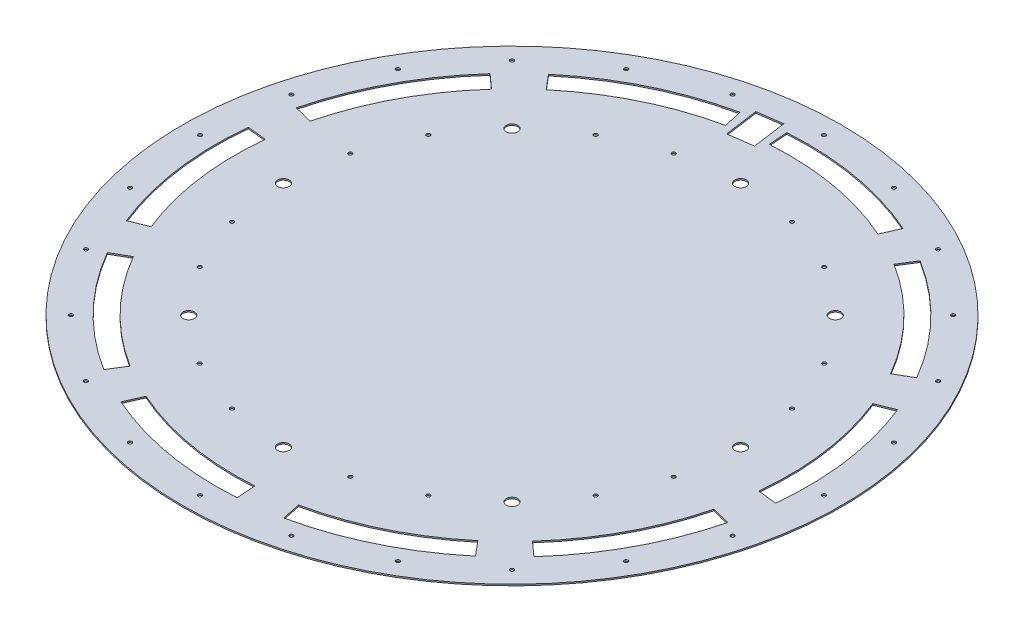
SolidWorks part; units mm, degrees
ref_plane "Front Plane" through (0, 0, 0) normal (0, 0, 1) x (1, 0, 0)
ref_plane "Top Plane" through (0, 0, 0) normal (0, 1, 0) x (1, 0, 0)
ref_plane "Right Plane" through (0, 0, 0) normal (1, 0, 0) x (0, 0, -1)
sketch "Sketch1" plane through (0, 0, 0) normal (0, 1, 0) x (1, 0, 0)
  line L0 (0, -1000) -> (0, 49000) construction
  line L1 (-1000, 0) -> (49000, 0) construction
  line L2 (0, 0) -> (-231.8222, 62.1166) construction
  line L3 (-231.8222, 62.1166) -> (-316.3407, 84.7632) construction
  line L4 (0, 0) -> (-45.5792, 324.3128) construction
  line L5 (-57.1305, 313.096) -> (-31.3836, 316.7145)
  line L6 (-31.3836, 316.7145) -> (-26.3733, 281.0648)
  line L7 (-26.3733, 281.0648) -> (-52.1203, 277.4463)
  line L8 (-52.1203, 277.4463) -> (-57.1305, 313.096)
  line L9 (-52.1203, 277.4463) -> (-31.3836, 316.7145) construction
  line L10 (-57.1305, 313.096) -> (-26.3733, 281.0648) construction
  line L11 (-20.2991, 290.2911) -> (-21.6943, 310.2424)
  line L13 (126.4951, 284.1126) -> (118.3604, 265.8417)
  line L14 (0, 0) -> (118.3604, 265.8417) construction
  line L15 (269.3339, 155.5) -> (252.0134, 145.5)
  line L16 (154.2065, 246.782) -> (164.8049, 263.743)
  line L17 (309.2963, -32.5084) -> (289.4059, -30.4178)
  line L18 (269.8105, 109.0105) -> (288.3542, 116.5027)
  line L19 (231.118, -208.0996) -> (216.2551, -194.717)
  line L20 (282.3561, -70.3993) -> (301.762, -75.2377)
  line L21 (64.6605, -304.2039) -> (60.5023, -284.641)
  line L22 (187.0512, -222.9189) -> (199.9069, -238.2398)
  line L23 (-126.4951, -284.1126) -> (-118.3604, -265.8417)
  line L24 (20.2991, -290.2911) -> (21.6943, -310.2424)
  line L25 (-269.3339, -155.5) -> (-252.0134, -145.5)
  line L26 (-154.2065, -246.782) -> (-164.8049, -263.743)
  line L27 (-309.2963, 32.5084) -> (-289.4059, 30.4178)
  line L28 (-269.8105, -109.0105) -> (-288.3542, -116.5027)
  line L29 (-231.118, 208.0996) -> (-216.2551, 194.717)
  line L30 (-282.3561, 70.3993) -> (-301.762, 75.2377)
  line L31 (-64.6605, 304.2039) -> (-60.5023, 284.641)
  line L32 (-187.0512, 222.9189) -> (-199.9069, 238.2398)
  circle A0 centre (0, 0) radius 346
  circle A2 centre (0, 240) radius 6
  circle A3 centre (169.7056, 169.7056) radius 6
  circle A4 centre (240, 0) radius 6
  circle A5 centre (169.7056, -169.7056) radius 6
  circle A6 centre (0, -240) radius 6
  circle A7 centre (-169.7056, -169.7056) radius 6
  circle A8 centre (-240, 0) radius 6
  circle A9 centre (-169.7056, 169.7056) radius 6
  circle A10 centre (0, 0) radius 240 construction
  circle A11 centre (-231.8222, 62.1166) radius 2
  circle A12 centre (-207.8461, 120.0003) radius 2
  circle A14 centre (-119.9997, 207.8468) radius 2
  circle A15 centre (-62.1161, 231.8231) radius 2
  circle A17 centre (62.1176, 231.8232) radius 2
  circle A18 centre (120.0013, 207.8471) radius 2
  circle A20 centre (207.8478, 120.0007) radius 2
  circle A21 centre (231.8241, 62.1171) radius 2
  circle A23 centre (231.8242, -62.1166) radius 2
  circle A24 centre (207.8481, -120.0003) radius 2
  circle A26 centre (120.0017, -207.8468) radius 2
  circle A27 centre (62.1181, -231.8231) radius 2
  circle A29 centre (-62.1156, -231.8232) radius 2
  circle A30 centre (-119.9993, -207.8471) radius 2
  circle A32 centre (-207.8458, -120.0007) radius 2
  circle A33 centre (-231.8221, -62.1171) radius 2
  arc A35 (-168.2848, -171.1146) -> (-171.1133, -168.2862) centre (-169.7051, -169.7065) ccw [skipped]
  arc A36 (-1.9987, -239.9917) -> (0, -242.001) centre (0.0013, -240.001) ccw [skipped]
  arc A37 (168.2862, -171.1133) -> (171.1146, -168.2849) centre (169.7075, -169.7061) ccw [skipped]
  arc A38 (238.002, 0) -> (239.9917, -1.9997) centre (240.002, 0.0003) ccw [skipped]
  arc A39 (171.1142, 168.2852) -> (168.2859, 171.1136) centre (169.7071, 169.7065) ccw [skipped]
  arc A40 (-1.9992, 239.9917) -> (-1.4433, 238.6172) centre (0.0007, 240.001) ccw [skipped]
  arc A41 (-168.2852, 171.1142) -> (-171.1136, 168.2859) centre (-169.7055, 169.7061) ccw [skipped]
  arc A42 (-239.9917, -2.0002) -> (-238, 0) centre (-240, -0.0003) ccw [skipped]
  circle A43 centre (0, 0) radius 327.5 construction
  circle A44 centre (-316.3407, 84.7632) radius 2
  circle A45 centre (-283.6233, 163.75) radius 2
  circle A46 centre (-231.5775, 231.5775) radius 2
  circle A47 centre (-163.75, 283.6233) radius 2
  circle A48 centre (-84.7632, 316.3407) radius 2
  circle A49 centre (0, 327.5) radius 2
  circle A50 centre (84.7632, 316.3407) radius 2
  circle A51 centre (163.75, 283.6233) radius 2
  circle A52 centre (231.5775, 231.5775) radius 2
  circle A53 centre (283.6233, 163.75) radius 2
  circle A54 centre (316.3407, 84.7632) radius 2
  circle A55 centre (327.5, 0) radius 2
  circle A56 centre (316.3407, -84.7632) radius 2
  circle A57 centre (283.6233, -163.75) radius 2
  circle A58 centre (231.5775, -231.5775) radius 2
  circle A59 centre (163.75, -283.6233) radius 2
  circle A60 centre (84.7632, -316.3407) radius 2
  circle A61 centre (0, -327.5) radius 2
  circle A62 centre (-84.7632, -316.3407) radius 2
  circle A63 centre (-163.75, -283.6233) radius 2
  circle A64 centre (-231.5775, -231.5775) radius 2
  circle A65 centre (-283.6233, -163.75) radius 2
  circle A66 centre (-316.3407, -84.7632) radius 2
  circle A67 centre (-327.5, 0) radius 2
  circle A68 centre (0, 0) radius 300 construction
  circle A71 centre (0, 0) radius 291 construction
  circle A72 centre (0, 0) radius 311 construction
  arc A74 (-20.2991, 290.2911) -> (118.3604, 265.8417) centre (0, 0) cw
  arc A75 (-21.6943, 310.2424) -> (126.4951, 284.1126) centre (0, 0) cw
  arc A76 (154.2065, 246.782) -> (252.0134, 145.5) centre (0, 0) cw
  arc A77 (164.8049, 263.743) -> (269.3339, 155.5) centre (0, 0) cw
  arc A78 (269.8105, 109.0105) -> (289.4059, -30.4178) centre (0, 0) cw
  arc A79 (288.3542, 116.5027) -> (309.2963, -32.5084) centre (0, 0) cw
  arc A80 (282.3561, -70.3993) -> (216.2551, -194.717) centre (0, 0) cw
  arc A81 (301.762, -75.2377) -> (231.118, -208.0996) centre (0, 0) cw
  arc A82 (187.0512, -222.9189) -> (60.5023, -284.641) centre (0, 0) cw
  arc A83 (199.9069, -238.2398) -> (64.6605, -304.2039) centre (0, 0) cw
  arc A84 (20.2991, -290.2911) -> (-118.3604, -265.8417) centre (0, 0) cw
  arc A85 (21.6943, -310.2424) -> (-126.4951, -284.1126) centre (0, 0) cw
  arc A86 (-154.2065, -246.782) -> (-252.0134, -145.5) centre (0, 0) cw
  arc A87 (-164.8049, -263.743) -> (-269.3339, -155.5) centre (0, 0) cw
  arc A88 (-269.8105, -109.0105) -> (-289.4059, 30.4178) centre (0, 0) cw
  arc A89 (-288.3542, -116.5027) -> (-309.2963, 32.5084) centre (0, 0) cw
  arc A90 (-282.3561, 70.3993) -> (-216.2551, 194.717) centre (0, 0) cw
  arc A91 (-301.762, 75.2377) -> (-231.118, 208.0996) centre (0, 0) cw
  arc A92 (-187.0512, 222.9189) -> (-60.5023, 284.641) centre (0, 0) cw
  arc A93 (-199.9069, 238.2398) -> (-64.6605, 304.2039) centre (0, 0) cw
  point P26 (0, 0)
  point P29 (0, 0)
  point P78 (0.001, 0)
  point P137 (0, 0)
  point P139 (-41.7519, 297.0804)
  point P190 (0, 0)
  dimension "D1" = 692
  dimension "D3" = 240
  dimension "D4" = 12
  dimension "D8" = 4
  dimension "D9" = 655
  dimension "D11" = 4
  dimension "D13" = 480
  dimension "D14" = 12
  dimension "D17" = 24
  dimension "D20" = 4
  dimension "D22" = 311
  dimension "D23" = 20
  dimension "D6" = 15
  dimension "D10" = 15
  dimension "D15" = 8
  dimension "D16" = 300
  dimension "D18" = 36
  dimension "D19" = 26
  dimension "D21" = 10
  dimension "D5" = 8
  dimension "D7" = 24
  dimension "D12" = 24
extrude "Boss-Extrude1" add sketch "Sketch1" along normal mid plane 1.5
